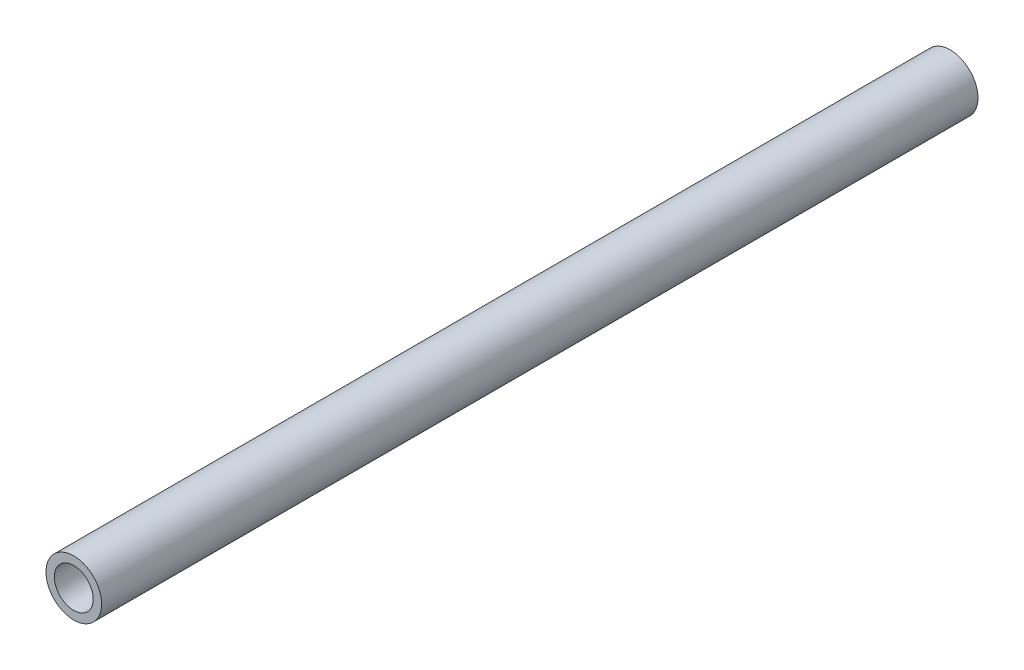
SolidWorks part; units mm, degrees
ref_plane "Front Plane" through (0, 0, 0) normal (1, 0, 0) x (0, 1, 0)
ref_plane "Top Plane" through (0, 0, 0) normal (0, 0, 1) x (0, 1, 0)
ref_plane "Right Plane" through (0, 0, 0) normal (0, 1, 0) x (-1, 0, 0)
sketch "Sketch1" plane through (0, 0, 0) normal (0, 0, 1) x (0, 1, 0)
  circle A0 centre (0, 0) radius 15.875
  circle A1 centre (0, 0) radius 11.1
  dimension "D1" = 31.75
  dimension "D2" = 22.2
extrude "Boss-Extrude1" add sketch "Sketch1" along normal blind 500
equation "\"OD\"= 1.25in"
equation "\"ID\"= 22.2"
equation "\"D1@Sketch1\"=\"OD\""
equation "\"D2@Sketch1\"=\"ID\""
equation "\"L\"= 500mm"
equation "\"D1@Boss-Extrude1\"=\"L\""
